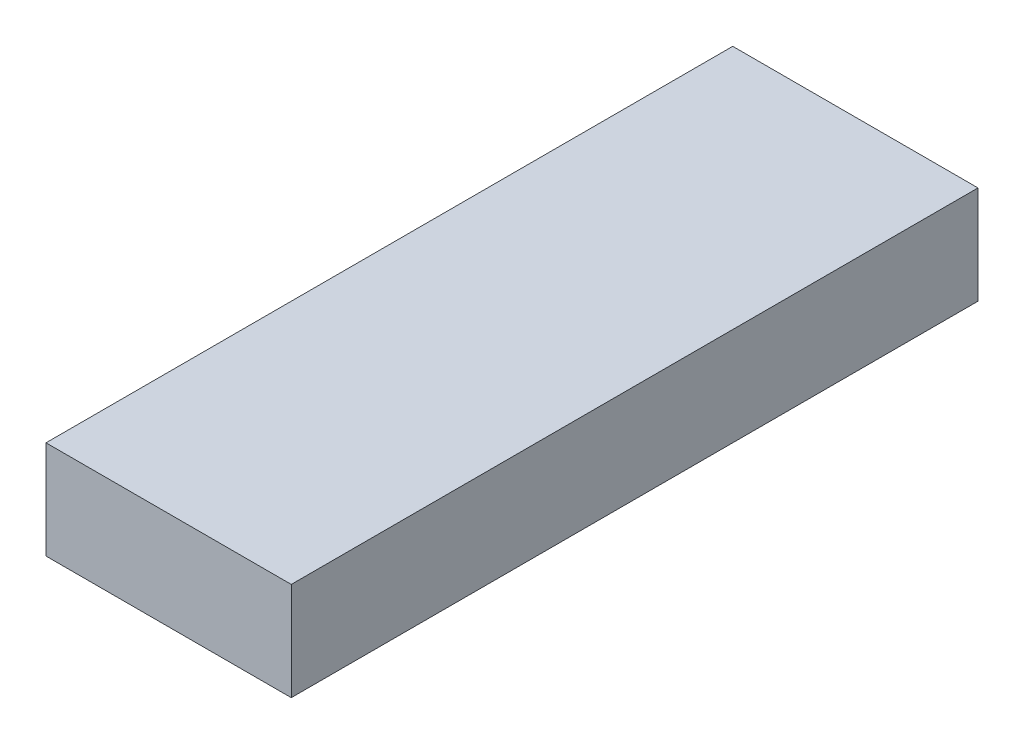
SolidWorks part; units mm, degrees
ref_plane "Front Plane" through (0, 0, 0) normal (0, 0, 1) x (1, 0, 0)
ref_plane "Top Plane" through (0, 0, 0) normal (0, 1, 0) x (1, 0, 0)
ref_plane "Right Plane" through (0, 0, 0) normal (1, 0, 0) x (0, 0, -1)
sketch "Sketch1" plane through (0, 0, 0) normal (0, 1, 0) x (1, 0, 0)
  line L1 (12.5, -35) -> (-12.5, -35)
  line L2 (12.5, -35) -> (12.5, 35)
  line L3 (12.5, 35) -> (-12.5, 35)
  line L4 (-12.5, -35) -> (-12.5, 35)
  line L5 (12.5, -35) -> (-12.5, 35) construction
  line L6 (12.5, 35) -> (-12.5, -35) construction
  point P0 (0, 0)
  dimension "D1" = 25
  dimension "D2" = 70
extrude "Boss-Extrude1" add sketch "Sketch1" along normal blind 10
